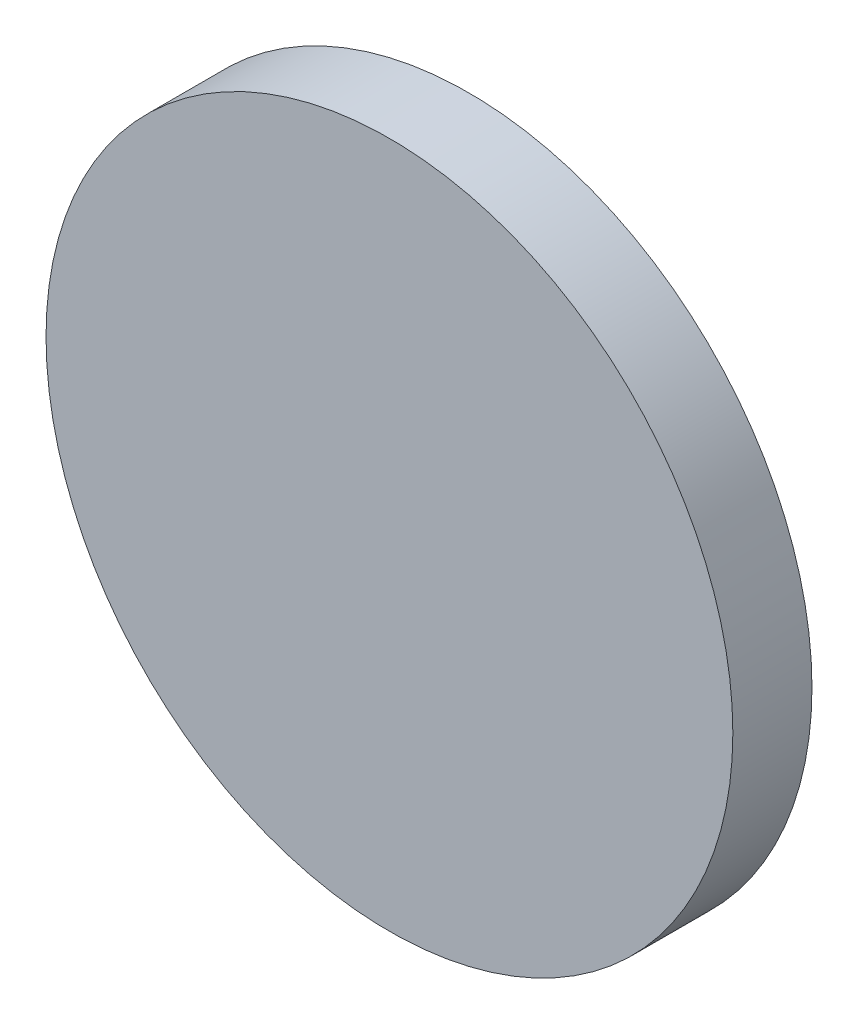
SolidWorks part; units mm, degrees
ref_plane "Front Plane" through (0, 0, 0) normal (0, 0, 1) x (1, 0, 0)
ref_plane "Top Plane" through (0, 0, 0) normal (0, 1, 0) x (1, 0, 0)
ref_plane "Right Plane" through (0, 0, 0) normal (1, 0, 0) x (0, 0, -1)
sketch "Sketch1" plane through (0, 0, 0) normal (0, 0, 1) x (1, 0, 0)
  circle A0 centre (0, 0) radius 22.0472
  dimension "D1" = 44.0944
extrude "Extrude1" add sketch "Sketch1" along normal blind 5.08
